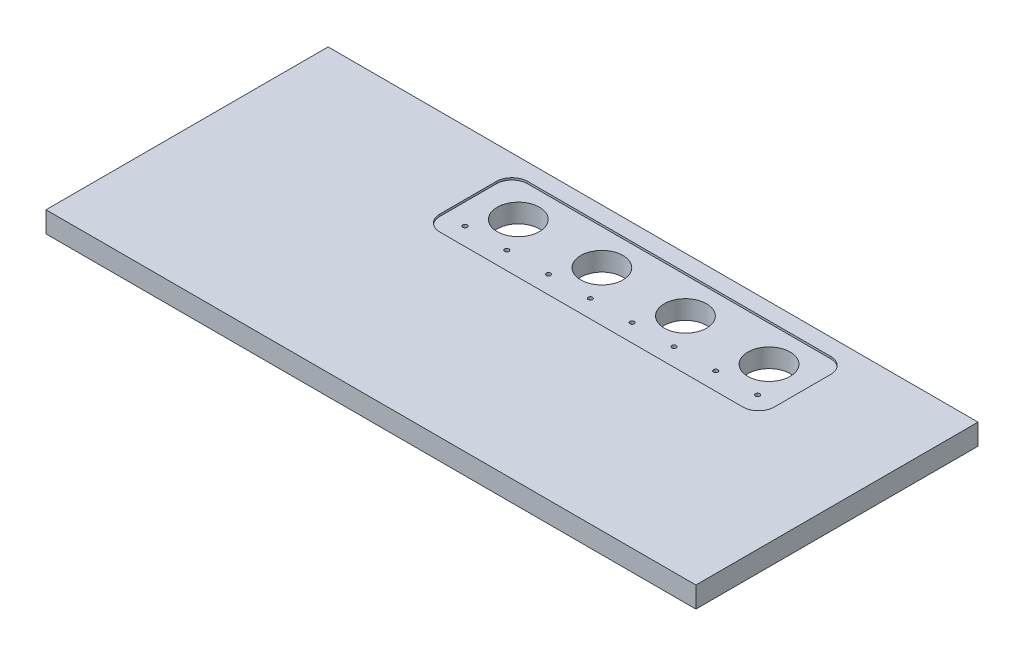
SolidWorks part; units mm, degrees
ref_plane "前视基准面" through (0, 0, 0) normal (0, 0, 1) x (1, 0, 0)
ref_plane "上视基准面" through (0, 0, 0) normal (0, 1, 0) x (1, 0, 0)
ref_plane "右视基准面" through (0, 0, 0) normal (1, 0, 0) x (0, 0, -1)
sketch "草图1" plane through (0, 0, 0) normal (0, 1, 0) x (1, 0, 0)
  line L5 (311, -135) -> (-311, -135)
  line L6 (311, -135) -> (311, 135)
  line L7 (311, 135) -> (-311, 135)
  line L8 (-311, -135) -> (-311, 135)
  line L9 (311, -135) -> (-311, 135) construction
  line L10 (311, 135) -> (-311, -135) construction
  point P0 (0, 0)
  dimension "D1" = 622
  dimension "D2" = 270
extrude "凸台-拉伸1" add sketch "草图1" along normal blind 20
sketch "草图2" plane through (0, 20, 0) normal (0, 1, 0) x (1, 0, 0)
  line L0 (-311, 135) -> (-311, -135) construction
  line L1 (-119, 119) -> (201, 119)
  line L2 (-119, 119) -> (-119, 35)
  line L3 (-119, 35) -> (201, 35)
  line L4 (201, 119) -> (201, 35)
  line L5 (311, 135) -> (-311, 135) construction
  dimension "D1" = 192
  dimension "D2" = 320
  dimension "D3" = 16
  dimension "D4" = 84
extrude "切除-拉伸1" cut sketch "草图2" against normal blind 2
sketch "草图3" plane through (0, 18, 0) normal (0, 1, 0) x (1, 0, 0)
  line L0 (-119, 119) -> (-119, 35) construction
  line L1 (311, 135) -> (-311, 135) construction
  circle A0 centre (-79, 85) radius 20.25
  circle A1 centre (1, 85) radius 20.25
  circle A2 centre (81, 85) radius 20.25
  circle A3 centre (161, 85) radius 20.25
  point P7 (0, 0)
  point P13 (0, 0)
  point P14 (0, 85)
  dimension "D3" = 40.5
  dimension "D1" = 40
  dimension "D2" = 50
  dimension "D5" = 80
  dimension "D4" = 4
extrude "切除-拉伸2" cut sketch "草图3" against normal up to next
sketch "草图4" plane through (0, 18, 0) normal (0, 1, 0) x (1, 0, 0)
  line L0 (-79, 85) -> (-79, -18.2826) construction
  circle A0 centre (-99, 54) radius 2.1
  circle A1 centre (-79, 85) radius 20.25 construction
  circle A2 centre (-79, 85) radius 20.25
  circle A3 centre (-59, 54) radius 2.1
  circle A4 centre (-19, 54) radius 2.1
  circle A5 centre (21, 54) radius 2.1
  circle A6 centre (61, 54) radius 2.1
  circle A7 centre (101, 54) radius 2.1
  circle A8 centre (141, 54) radius 2.1
  circle A9 centre (181, 54) radius 2.1
  dimension "D2" = 4.2
  dimension "D1" = 31
  dimension "D3" = 20
  dimension "D4" = 20
  dimension "D6" = 40
  dimension "D5" = 4
extrude "切除-拉伸3" cut sketch "草图4" against normal blind 10
fillet "圆角1" radius 15 4 edges at (-119, 19, -35) (201, 19, -35) (201, 19, -119) (-119, 19, -119)
sketch "草图5" plane through (0, 0, 0) normal (0, -1, 0) x (1, 0, 0)
  line L0 (311, -135) -> (-311, -135) construction
  line L1 (-311, -135) -> (-311, 135) construction
  circle A0 centre (274, -30) radius 3.35
  circle A1 centre (262, -5) radius 3.35
  circle A2 centre (109, -30) radius 3.35
  circle A3 centre (-56, -30) radius 3.35
  circle A4 centre (-221, -30) radius 3.35
  circle A5 centre (-138, -5) radius 3.35
  circle A6 centre (62, -5) radius 3.35
  circle A7 centre (274, 70) radius 3.35
  circle A8 centre (109, 70) radius 3.35
  circle A9 centre (-56, 70) radius 3.35
  circle A10 centre (-221, 70) radius 3.35
  point P24 (0, 0)
  point P25 (0, 0)
  point P26 (0, 0)
  point P27 (0, 0)
  point P28 (0, 0)
  point P29 (0, 0)
  point P30 (0, 0)
  point P31 (0, 0)
  dimension "D9" = 6.7
  dimension "D1" = 105
  dimension "D2" = 130
  dimension "D3" = 100
  dimension "D4" = 165
  dimension "D5" = 165
  dimension "D6" = 165
  dimension "D7" = 200
  dimension "D8" = 200
  dimension "D10" = 90
  dimension "D11" = 173
extrude "切除-拉伸4" cut sketch "草图5" against normal blind 12
